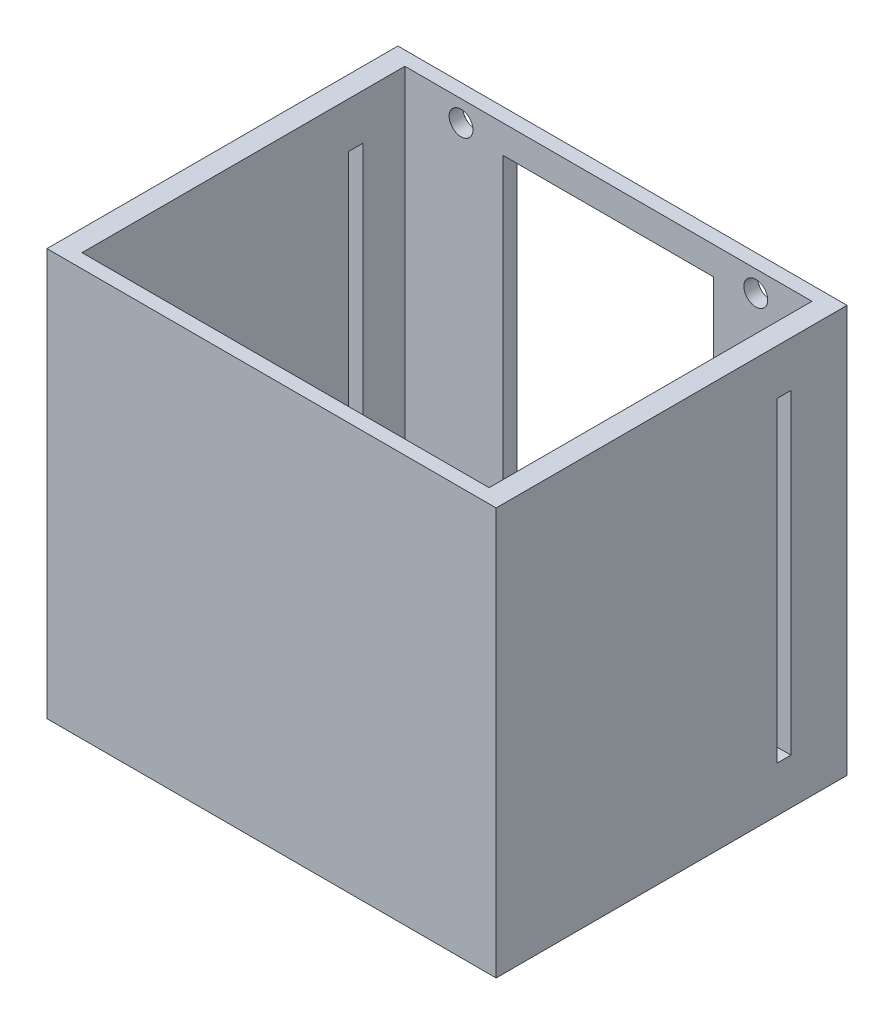
SolidWorks part; units mm, degrees
ref_plane "前视基准面" through (0, 0, 0) normal (0, 0, 1) x (1, 0, 0)
ref_plane "上视基准面" through (0, 0, 0) normal (0, 1, 0) x (1, 0, 0)
ref_plane "右视基准面" through (0, 0, 0) normal (1, 0, 0) x (0, 0, -1)
sketch "草图1" plane through (0, 0, 0) normal (0, 1, 0) x (1, 0, 0)
  line L1 (32, -25) -> (-32, -25)
  line L2 (32, -25) -> (32, 25)
  line L3 (32, 25) -> (-32, 25)
  line L4 (-32, -25) -> (-32, 25)
  line L5 (32, -25) -> (-32, 25) construction
  line L6 (32, 25) -> (-32, -25) construction
  point P0 (0, 0)
  dimension "D1" = 64
  dimension "D2" = 50
extrude "凸台-拉伸2" add sketch "草图1" along normal blind 58
sketch "草图2" plane through (0, 0, 0) normal (0, -1, 0) x (1, 0, 0)
  line L0 (-32, 25) -> (32, 25) construction
  line L1 (29, -23) -> (-29, -23)
  line L2 (29, -23) -> (29, 23)
  line L3 (29, 23) -> (-29, 23)
  line L4 (-29, -23) -> (-29, 23)
  line L5 (29, -23) -> (-29, 23) construction
  line L6 (29, 23) -> (-29, -23) construction
  point P0 (0, 0)
  dimension "D1" = 58
  dimension "D2" = 46
  dimension "D3" = 2
extrude "切除-拉伸1" cut sketch "草图2" against normal through all
sketch "草图5" plane through (29, 0, 0) normal (-1, 0, 0) x (0, 0, 1)
  line L0 (-23, 29) -> (23, 29) construction
  line L1 (-23, 58) -> (-23, 0) construction
  line L2 (23, 58) -> (23, 0) construction
  line L3 (-25, 58) -> (-25, 0) construction
  line L4 (-15, 6.5) -> (-17, 6.5)
  line L5 (-15, 6.5) -> (-15, 51.5)
  line L6 (-15, 51.5) -> (-17, 51.5)
  line L7 (-17, 6.5) -> (-17, 51.5)
  line L8 (-15, 6.5) -> (-17, 51.5) construction
  line L9 (-15, 51.5) -> (-17, 6.5) construction
  point P6 (-16, 29)
  dimension "D1" = 45
  dimension "D2" = 2
  dimension "D3" = 8
  dimension "D4" = 6
extrude "切除-拉伸2" cut sketch "草图5" against normal blind 50
sketch "草图6" plane through (-29, 0, 0) normal (1, 0, 0) x (0, 0, -1)
  line L0 (23, 29) -> (-23, 29) construction
  line L1 (23, 58) -> (23, 0) construction
  line L2 (-23, 58) -> (-23, 0) construction
  line L4 (15, 51.5) -> (17, 51.5)
  line L5 (15, 51.5) -> (15, 6.5)
  line L6 (15, 6.5) -> (17, 6.5)
  line L7 (17, 51.5) -> (17, 6.5)
  line L8 (15, 51.5) -> (17, 6.5) construction
  line L9 (15, 6.5) -> (17, 51.5) construction
  point P6 (16, 29)
  dimension "D1" = 45
  dimension "D2" = 2
  dimension "D3" = 6
extrude "切除-拉伸3" cut sketch "草图6" against normal blind 50
hole_wizard "M3 间隙孔1" positions "草图7" profile "草图8" hole size "M3" standard "GB"
sketch "草图7" plane through (0, 0, -25) normal (0, 0, -1) x (-1, 0, 0)
  line L0 (-32, 29) -> (32, 29) construction
  line L1 (-32, 58) -> (-32, 0) construction
  line L2 (32, 58) -> (32, 0) construction
  line L4 (0, 58) -> (0, 0) construction
  line L5 (-32, 58) -> (32, 58) construction
  point P0 (-21, 55)
  point P2 (-21, 3)
  point P4 (21, 3)
  point P6 (21, 55)
  dimension "D1" = 21
  dimension "D2" = 21
  dimension "D3" = 26
  dimension "D4" = 26
  dimension "D5" = 26
  dimension "D6" = 26
  dimension "D7" = 21
  dimension "D8" = 21
sketch "草图8" plane through (21, 55, -25) normal (1, 0, 0) x (0, 1, 0)
  line L0 (0, 0) -> (0, 6.0215)
  line L1 (0, 6.0215) -> (1.7, 5)
  line L2 (1.7, 5) -> (1.7, 0.025)
  line L3 (1.7, 0.025) -> (1.725, 0)
  line L5 (1.725, 0) -> (0, 0)
  line L6 (-1.7, 0.025) -> (-1.725, 0) construction
  line L10 (0, 6.0215) -> (-1.7, 5) construction
  line L11 (0, -6.35) -> (0, 107.95) construction
  dimension "孔直径" = 3.4
  dimension "孔深度" = 5
  dimension "近端锥形沉头孔直径" = 3.45
  dimension "近端锥形沉头孔角度" = 90
  dimension "导头角度" = 118
sketch "草图9" plane through (0, 0, -25) normal (0, 0, -1) x (-1, 0, 0)
  line L0 (-32, 29) -> (32, 29) construction
  line L1 (-32, 58) -> (-32, 0) construction
  line L2 (32, 58) -> (32, 0) construction
  line L3 (0, 58) -> (0, 0) construction
  line L4 (-32, 58) -> (32, 58) construction
  line L6 (15, 4) -> (-15, 4)
  line L7 (15, 4) -> (15, 54)
  line L8 (15, 54) -> (-15, 54)
  line L9 (-15, 4) -> (-15, 54)
  line L10 (15, 4) -> (-15, 54) construction
  line L11 (15, 54) -> (-15, 4) construction
  point P11 (0, 29)
  dimension "D1" = 30
  dimension "D2" = 50
extrude "切除-拉伸4" cut sketch "草图9" against normal blind 30
